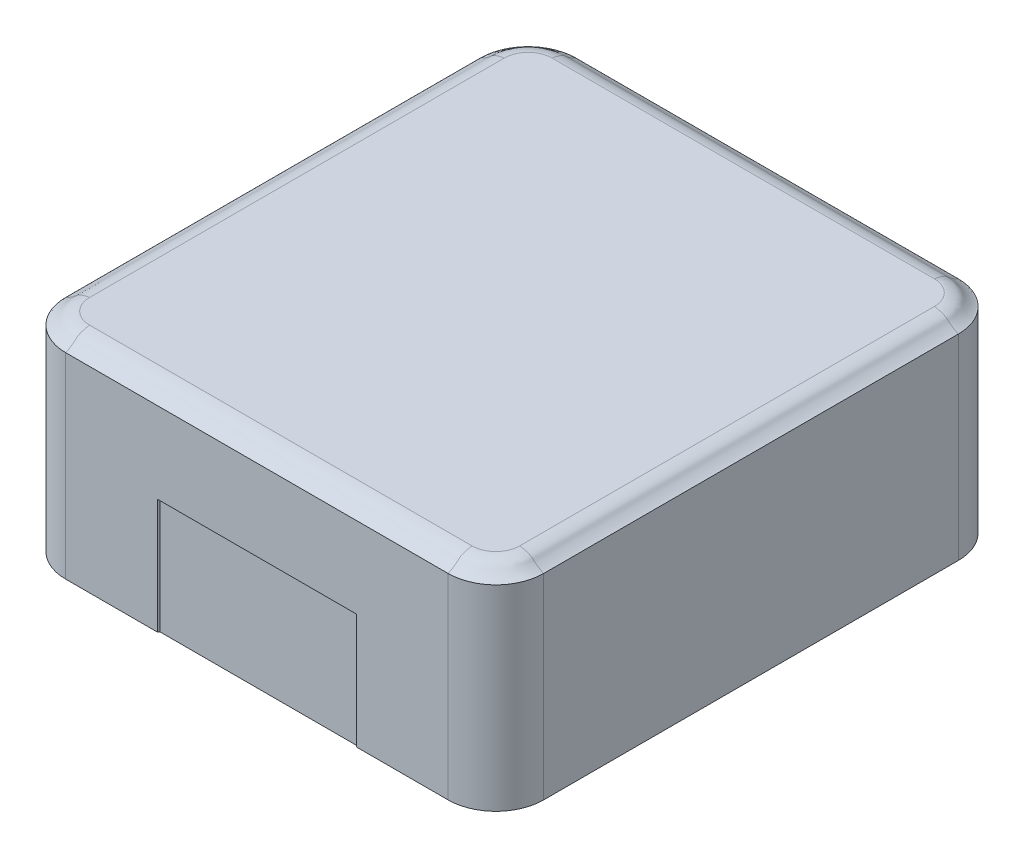
SolidWorks part; units mm, degrees
ref_plane "前视基准面" through (0, 0, 0) normal (0, 0, 1) x (1, 0, 0)
ref_plane "上视基准面" through (0, 0, 0) normal (0, 1, 0) x (1, 0, 0)
ref_plane "右视基准面" through (0, 0, 0) normal (1, 0, 0) x (0, 0, -1)
sketch "草图1" plane through (0, 0, 0) normal (0, 1, 0) x (1, 0, 0)
  line L1 (-6.3, 6.725) -> (6.3, 6.725)
  line L2 (-6.3, 6.725) -> (-6.3, -6.725)
  line L3 (-6.3, -6.725) -> (6.3, -6.725)
  line L4 (6.3, 6.725) -> (6.3, -6.725)
  line L5 (-6.3, 6.725) -> (6.3, -6.725) construction
  line L6 (-6.3, -6.725) -> (6.3, 6.725) construction
  point P0 (0, 0)
  dimension "D1" = 12.6
  dimension "D2" = 13.45
extrude "凸台-拉伸1" add sketch "草图1" along normal blind 5.8
fillet "圆角1" radius 1.26 4 edges at (6.3, 2.9, -6.725) (-6.3, 2.9, -6.725) (-6.3, 2.9, 6.725) (6.3, 2.9, 6.725)
sketch "草图2" plane through (0, 0, 0) normal (0, -1, 0) x (1, 0, 0)
  line L0 (0, 6.725) -> (0, -6.725) construction
  line L1 (-5.04, 6.725) -> (5.04, 6.725) construction
  line L2 (5.04, -6.725) -> (-5.04, -6.725) construction
  line L3 (6.3, 0) -> (-6.3, 0) construction
  line L4 (2.75, 4.225) -> (-2.75, 4.225)
  line L5 (2.75, 4.225) -> (2.75, 6.725)
  line L6 (2.75, 6.725) -> (-2.75, 6.725)
  line L7 (-2.75, 4.225) -> (-2.75, 6.725)
  line L8 (2.75, 4.225) -> (-2.75, 6.725) construction
  line L9 (2.75, 6.725) -> (-2.75, 4.225) construction
  line L10 (6.3, 5.465) -> (6.3, -5.465) construction
  line L11 (-6.3, -5.465) -> (-6.3, 5.465) construction
  line L12 (2.75, -6.725) -> (-2.75, -4.225) construction
  line L13 (2.75, -4.225) -> (-2.75, -6.725) construction
  line L14 (-2.75, -4.225) -> (-2.75, -6.725)
  line L15 (2.75, -6.725) -> (-2.75, -6.725)
  line L16 (2.75, -4.225) -> (2.75, -6.725)
  line L17 (2.75, -4.225) -> (-2.75, -4.225)
  point P6 (0, 5.475)
  point P21 (0, -5.475)
  dimension "D1" = 5.5
  dimension "D2" = 2.5
extrude "切除-拉伸1" cut sketch "草图2" against normal blind 0.15
ref_plane "基准面1" through (-5.04, 0, 0) normal (1, 0, 0) x (0, 0, -1)
sketch "草图3" plane through (-5.04, 0, 0) normal (1, 0, 0) x (0, 0, -1)
  line L0 (-6.725, 5.8) -> (-6.725, 0) construction
  line L1 (-5.465, 5.8) -> (-6.725, 5.8) construction
  line L2 (-6.095, 5.8) -> (-6.725, 5.8)
  line L3 (-6.725, 5.8) -> (-6.725, 5.485)
  line L4 (5.465, 5.8) -> (-5.465, 5.8) construction
  line L5 (-6.41, 5.8) -> (-6.41, 5.6992) construction
  line L6 (-6.725, 5.6425) -> (-6.473, 5.6425) construction
  spline S0 degree 3 poles (-6.095, 5.8) (-6.1153, 5.8) (-6.3692, 5.7571) (-6.5082, 5.5955) (-6.7092, 5.485) (-6.725, 5.485) knots 0 0 0 0 0.464083 0.583014 1 1 1 1
  dimension "D1" = 0.63
  dimension "D2" = 0.315
  dimension "D3" = 0.1008
  dimension "D4" = 0.252
curve "组合曲线1"
sweep "切除-扫描1" cut profiles "草图3" path "组合曲线1"
ref_plane "基准面2" through (0, 2.9, 0) normal (0, 1, 0) x (1, 0, 0)
mirror "镜向1" about plane through (0, 2.9, 0) normal (0, 1, 0) of "切除-扫描1"
sketch "草图4" plane through (0, 0.15, 0) normal (0, 1, 0) x (1, 0, 0)
  line L0 (0, -6.725) -> (0, -6.65) construction
  line L2 (5.04, -6.725) -> (-5.04, -6.725) construction
  line L8 (2.625, -6.65) -> (-2.625, -6.65)
  line L9 (2.625, -6.65) -> (2.625, -6.725)
  line L10 (2.625, -6.725) -> (-2.625, -6.725)
  line L11 (-2.625, -6.65) -> (-2.625, -6.725)
  line L12 (2.625, -6.65) -> (-2.625, -6.725) construction
  line L13 (2.625, -6.725) -> (-2.625, -6.65) construction
  point P5 (0, -6.6875)
  dimension "D1" = 5.25
  dimension "D2" = 0.075
extrude "切除-拉伸2" cut sketch "草图4" along normal blind 3.2
mirror "镜向2" about plane through (0, 0, 0) normal (0, 0, 1) of "切除-拉伸2"
equation "\"D1@草图1\"=\"A\""
equation "\"D2@草图1\"=\"B\""
equation "\"D1@凸台-拉伸1\"=\"C\""
equation "\"D1@圆角1\"=0.1*\"A\""
equation "\"D1@草图2\"=1.1*\"E\""
equation "\"D2@草图2\"=0.1*\"E\"+\"D\""
equation "\"D1@草图3\"=0.05*\"A\""
equation "\"D2@草图3\"=0.025*\"A\""
equation "\"A\"= 12.6mm'宽度"
equation "\"B\"= 13.45mm'长度"
equation "\"C\"= 5.8mm'高度"
equation "\"D\"= 2.0mm'引脚宽度"
equation "\"E\"= 5.0mm'引脚长度"
equation "\"F\"= 0.3mm'引脚厚度"
equation "\"D1@切除-拉伸1\"=0.5*\"F\""
equation "\"D1@切除-拉伸2\"=0.5*\"C\"+\"F\""
equation "\"D3@草图3\"=0.008*\"A\""
equation "\"D4@草图3\"=0.02*\"A\""
equation "\"D1@草图4\"=1.05*\"E\""
equation "\"D2@草图4\"=0.25*\"F\""
